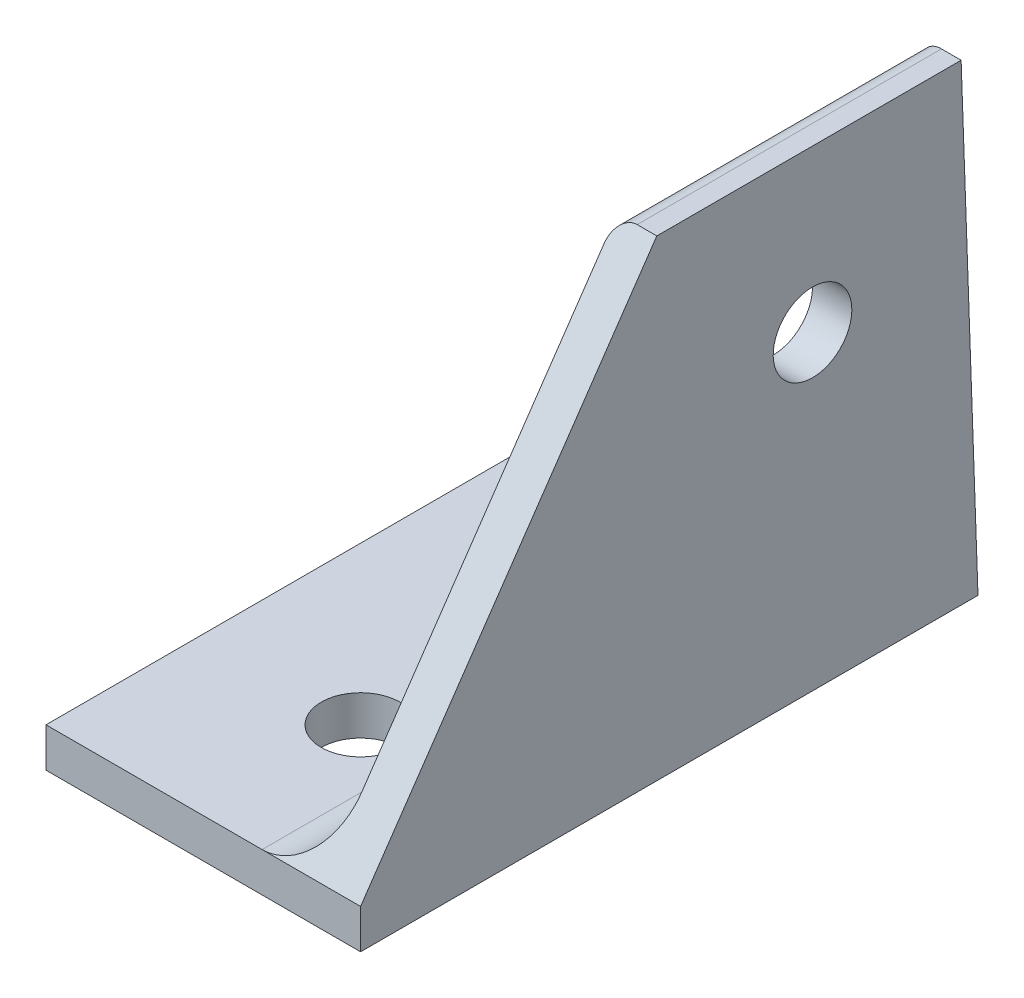
SolidWorks part; units mm, degrees
ref_plane "Front Plane" through (0, 0, 0) normal (0, 0, 1) x (1, 0, 0)
ref_plane "Top Plane" through (0, 0, 0) normal (0, 1, 0) x (1, 0, 0)
ref_plane "Right Plane" through (0, 0, 0) normal (1, 0, 0) x (0, 0, -1)
sketch "Sketch0" plane through (0, 0, 0) normal (0, 0, 1) x (1, 0, 0)
  line L0 (-19.05, -19.05) -> (19.05, -19.05)
  line L1 (19.05, -19.05) -> (19.05, 19.05)
  line L2 (19.05, 0) -> (0, 0) construction
  line L3 (0, 0) -> (0, -19.05) construction
  line L4 (15.875, -11.0998) -> (15.875, 19.05) construction
  line L5 (11.0998, -15.875) -> (-19.05, -15.875) construction
  arc A0 (15.875, -11.0998) -> (11.0998, -15.875) centre (11.0998, -11.0998) cw
  point P3 (14.4764, -14.4764)
  dimension "Inside Corner Radius" = 4.7752
  dimension "Outside Height" = 38.1
  dimension "Inside Height" = 34.925
  dimension "Inside Width" = 34.925
  dimension "Wall Thickness" = 3.175
  dimension "D1" = 3.175
  dimension "Outside Width" = 38.1
sketch "Sketch1" plane through (0, 0, 0) normal (1, 0, 0) x (0, 0, -1)
  line L0 (25.4, 0) -> (-25.4, 0)
  point P4 (0, 0)
  dimension "Length" = 50.8
sketch "Sketch2" plane through (0, 0, 0) normal (0, 0, 1) x (1, 0, 0)
  line L0 (-19.05, -19.05) -> (19.05, -19.05)
  line L1 (19.05, -19.05) -> (19.05, 19.05)
  line L2 (19.05, 19.05) -> (15.875, 19.05) construction
  line L3 (15.875, 17.4625) -> (15.875, -11.0998)
  line L4 (11.0998, -15.875) -> (-17.4625, -15.875)
  line L5 (-19.05, -19.05) -> (-19.05, -15.875) construction
  line L6 (17.4625, 19.05) -> (19.05, 19.05)
  line L7 (-19.05, -17.4625) -> (-19.05, -19.05)
  line L8 (19.05, 0) -> (0, 0) construction
  line L9 (0, 0) -> (0, -19.05) construction
  arc A0 (15.875, 17.4625) -> (17.4625, 19.05) centre (17.4625, 17.4625) cw
  arc A1 (-19.05, -17.4625) -> (-17.4625, -15.875) centre (-17.4625, -17.4625) cw
  arc A2 (15.875, -11.0998) -> (11.0998, -15.875) centre (11.0998, -11.0998) cw
  dimension "Inside Radius" = 4.7752
  dimension "Height" = 38.1
  dimension "Width" = 38.1
  dimension "Thickness" = 3.175
extrude "Boss-Extrude1" add sketch "Sketch2" along normal mid plane 50.8
sketch "Break Locations" plane through (0, 0, 0) normal (1, 0, 0) x (0, 0, -1)
  line L0 (13.462, 0) -> (-13.462, 0)
  line L1 (-25.4, -19.05) -> (-25.4, 19.05) construction
  line L2 (25.4, -19.05) -> (25.4, 19.05) construction
  point P0 (6.985, 0)
  point P1 (-6.985, 0)
  point P10 (0, 0)
  point P11 (-13.462, 0)
  point P13 (13.462, 0)
  dimension "D1" = 32.385
  dimension "D2" = 32.385
  dimension "D3" = 38.862
sketch "Sketch3" plane through (0, -19.05, 0) normal (0, -1, 0) x (1, 0, 0)
  line L0 (19.05, 25.4) -> (6.35, 25.4) construction
  line L1 (-19.05, 25.4) -> (19.05, 25.4) construction
  line L2 (6.35, 25.4) -> (6.35, 12.7) construction
  line L3 (6.35, 12.7) -> (6.35, -12.7) construction
  line L4 (-19.05, 25.4) -> (-6.35, 25.4)
  line L5 (-6.35, 25.4) -> (-6.35, -25.4)
  line L6 (-19.05, -25.4) -> (19.05, -25.4) construction
  line L7 (-6.35, -25.4) -> (-19.05, -25.4)
  line L8 (-19.05, -25.4) -> (-19.05, 25.4)
  circle A0 centre (6.35, 12.7) radius 3.175
  circle A1 centre (6.35, -12.7) radius 3.175
  dimension "D4" = 12.7
  dimension "D1" = 12.7
  dimension "D2" = 12.7
  dimension "D3" = 25.4
extrude "Cut-Extrude1" cut sketch "Sketch3" against normal through all
sketch "Sketch12" plane through (19.05, 0, 0) normal (1, 0, 0) x (0, 0, -1)
  line L0 (23.0872, 19.05) -> (24.4495, -19.05)
  line L1 (23.7342, -5.6191) -> (10.4495, 500.9368) construction
  line L2 (-25.4, 19.05) -> (25.4, 19.05) construction
  line L3 (-25.4, -19.05) -> (25.4, -19.05) construction
  line L5 (-1.4842, 19.05) -> (-25.4, -15.875)
  line L6 (-25.4, -19.05) -> (-25.4, 19.05) construction
  line L7 (-25.4, -15.875) -> (-25.4, -19.05)
  line L8 (-25.4, -19.05) -> (24.4495, -19.05)
  line L9 (23.0872, 19.05) -> (-1.4842, 19.05)
  dimension "D1" = 3.175
extrude "Cut-Extrude2" cut sketch "Sketch12" against normal through all flip side to cut
sketch "Sketch13" plane through (19.05, 0, 0) normal (1, 0, 0) x (0, 0, -1)
  line L0 (10.7562, 18.7176) -> (11.0886, 6.0219) construction
  circle A0 centre (11.0886, 6.0219) radius 3.175
extrude "Cut-Extrude3" cut sketch "Sketch13" against normal through all
sketch "Sketch14" plane through (0, -15.875, 0) normal (0, 1, 0) x (1, 0, 0)
  circle A0 centre (6.35, -12.7) radius 6.35
  circle A1 centre (6.35, 12.7) radius 6.35
extrude "Cut-Extrude4" cut sketch "Sketch14" along normal blind 2.54
equation "\"D1@Break Locations\" = .85 * \"Height@Sketch2\""
equation "\"D2@Break Locations\"=\"D1@Break Locations\""
equation "\"Thickness@Sketch2\"=\"wall thickness@sketch0\""
equation "\"Height@Sketch2\"=\"outside height@sketch0\""
equation "\"Width@Sketch2\"=\"outside width@sketch0\""
equation "\"Inside Radius@Sketch2\"=\"inside corner radius@sketch0\""
equation "\"Length@Boss-Extrude1\"=\"length@sketch1\""
equation "\"D3@Break Locations\"=\"D2@Break Locations\"*1.2"
equation "\"D1@Sketch0\"=\"Wall Thickness@Sketch0\""
